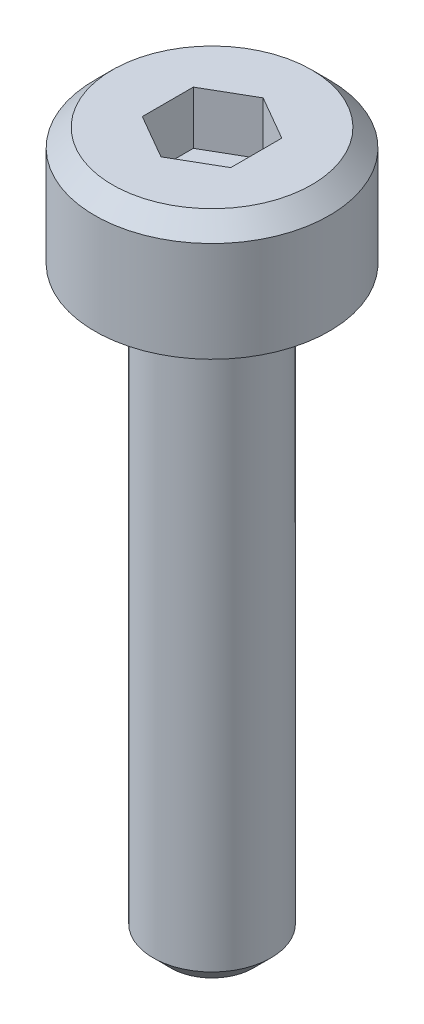
SolidWorks part; units mm, degrees
ref_plane "Front Plane" through (0, 0, 0) normal (0, 0, 1) x (1, 0, 0)
ref_plane "Top Plane" through (0, 0, 0) normal (0, 1, 0) x (1, 0, 0)
ref_plane "Right Plane" through (0, 0, 0) normal (1, 0, 0) x (0, 0, -1)
sketch "Sketch1" plane through (0, 0, 0) normal (0, 0, 1) x (1, 0, 0)
  line L0 (0, -10) -> (0.7, -10)
  line L1 (0.7, -10) -> (1, -9.7)
  line L2 (1, -9.7) -> (1, 0)
  line L3 (1, 0) -> (1.99, 0)
  line L4 (1.99, 0) -> (1.99, 1.7)
  line L5 (1.99, 1.7) -> (1.69, 2)
  line L6 (1.69, 2) -> (0, 2)
  line L7 (0, 2) -> (0, -10)
  line L8 (0, -10) -> (0, 1000) construction
revolve "Revolve1" add sketch "Sketch1" angle 360 about L8
cosmetic thread "Cosmetic Thread1" parameters "D1"=9.7, "D2"=1.567
ref_plane "Plane1" through (0, 2, 0) normal (0, 1, 0) x (1, 0, 0)
sketch "Sketch2" plane through (0, 2, 0) normal (0, 1, 0) x (1, 0, 0)
  line L0 (0.75, -0.433) -> (0, -0.866)
  line L1 (0, -0.866) -> (-0.75, -0.433)
  line L2 (-0.75, -0.433) -> (-0.75, 0.433)
  line L3 (-0.75, 0.433) -> (0, 0.866)
  line L4 (0, 0.866) -> (0.75, 0.433)
  line L5 (0.75, 0.433) -> (0.75, -0.433)
extrude "Cut-Extrude1" cut sketch "Sketch2" against normal blind 0.9
